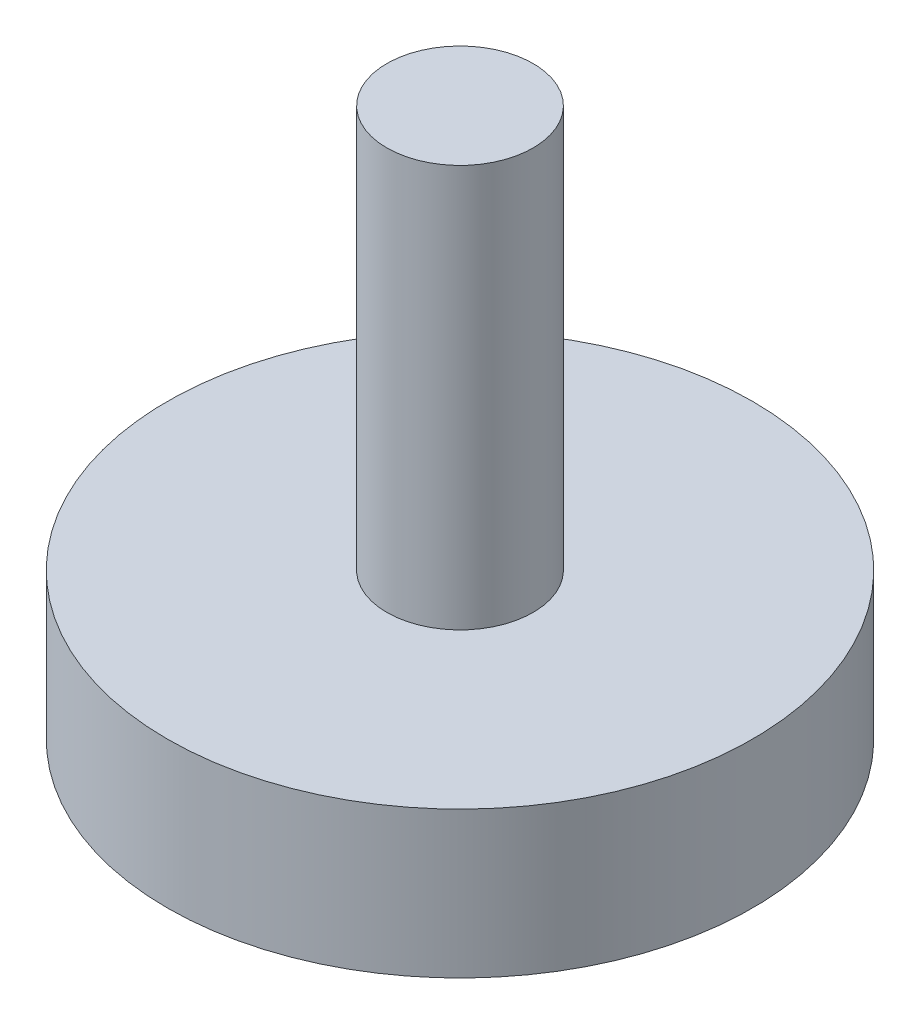
SolidWorks part; units mm, degrees
ref_plane "前视基准面" through (0, 0, 0) normal (0, 0, 1) x (1, 0, 0)
ref_plane "上视基准面" through (0, 0, 0) normal (0, 1, 0) x (1, 0, 0)
ref_plane "右视基准面" through (0, 0, 0) normal (1, 0, 0) x (0, 0, -1)
other "Configuration Table"
sketch "草图1" plane through (0, 0, 0) normal (0, 1, 0) x (1, 0, 0)
  circle A0 centre (0, 0) radius 40
  dimension "D1" = 80
extrude "凸台-拉伸1" add sketch "草图1" along normal blind 20
sketch "草图2" plane through (0, 20, 0) normal (0, 1, 0) x (1, 0, 0)
  circle A0 centre (0, 0) radius 10
  dimension "D1" = 20
extrude "凸台-拉伸2" add sketch "草图2" along normal blind 55
